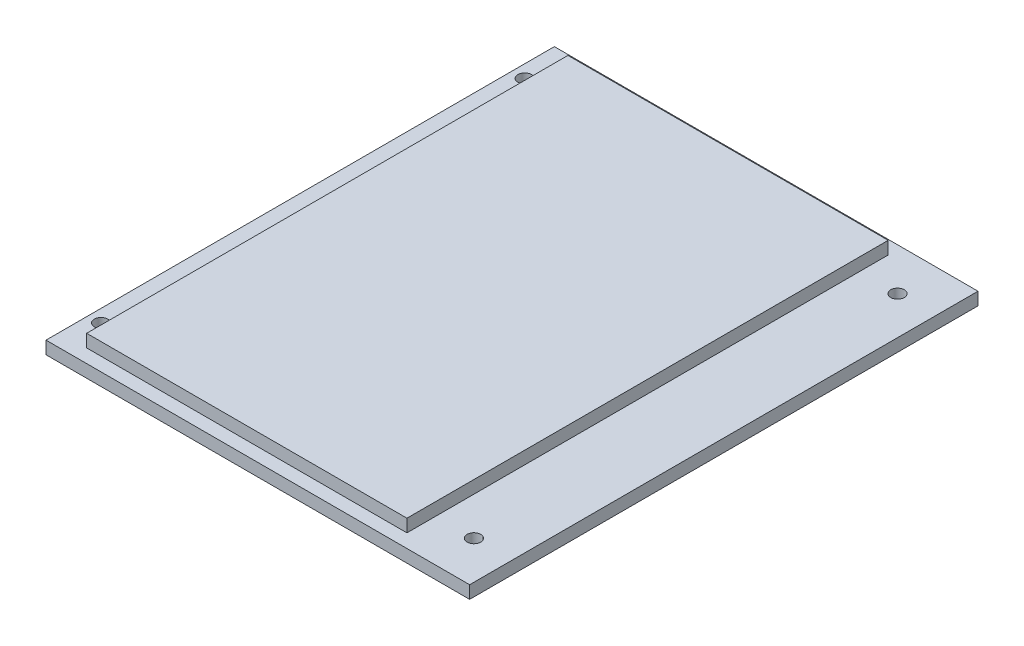
SolidWorks part; units mm, degrees
ref_plane "Спереди" through (0, 0, 0) normal (0, 0, 1) x (1, 0, 0)
ref_plane "Сверху" through (0, 0, 0) normal (0, 1, 0) x (1, 0, 0)
ref_plane "Справа" through (0, 0, 0) normal (1, 0, 0) x (0, 0, -1)
sketch "Sketch1" plane through (0, 0, 0) normal (0, 1, 0) x (1, 0, 0)
  line L1 (50, -60) -> (-50, -60)
  line L2 (50, -60) -> (50, 60)
  line L3 (50, 60) -> (-50, 60)
  line L4 (-50, -60) -> (-50, 60)
  line L5 (50, -60) -> (-50, 60) construction
  line L6 (50, 60) -> (-50, -60) construction
  point P0 (0, 0)
  dimension "D1" = 120
  dimension "D2" = 100
extrude "Boss-Extrude1" add sketch "Sketch1" along normal blind 3
sketch "Sketch2" plane through (0, 3, 0) normal (0, 1, 0) x (1, 0, 0)
  line L0 (-50, 0) -> (50, 0) construction
  line L1 (-50, 60) -> (-50, -60) construction
  line L2 (50, -60) -> (50, 60) construction
  line L4 (32, -56.8) -> (-43.6, -56.8)
  line L5 (32, -56.8) -> (32, 56.8)
  line L6 (32, 56.8) -> (-43.6, 56.8)
  line L7 (-43.6, -56.8) -> (-43.6, 56.8)
  line L8 (32, -56.8) -> (-43.6, 56.8) construction
  line L9 (32, 56.8) -> (-43.6, -56.8) construction
  point P6 (-5.8, 0)
  point P12 (-50, 0)
  dimension "D1" = 113.6
  dimension "D2" = 75.6
  dimension "D3" = 18
extrude "Boss-Extrude2" add sketch "Sketch2" along normal blind 3
sketch "Sketch3" plane through (0, 3, 0) normal (0, 1, 0) x (1, 0, 0)
  line L0 (41, 60) -> (41, -60) construction
  line L1 (50, 60) -> (-50, 60) construction
  line L2 (-50, -60) -> (50, -60) construction
  line L3 (-47, -60) -> (-47, 60) construction
  circle A0 centre (41, -50) radius 1.6
  circle A1 centre (41, 50) radius 1.6
  circle A2 centre (-47, -50) radius 1.6
  circle A3 centre (-47, 50) radius 1.6
  point P18 (41, 0)
  point P19 (-47, 0)
  dimension "D3" = 3.2
  dimension "D1" = 9
  dimension "D2" = 3
  dimension "D4" = 100
  dimension "D5" = 50
  dimension "D6" = 100
  dimension "D7" = 50
extrude "Cut-Extrude1" cut sketch "Sketch3" against normal through all
